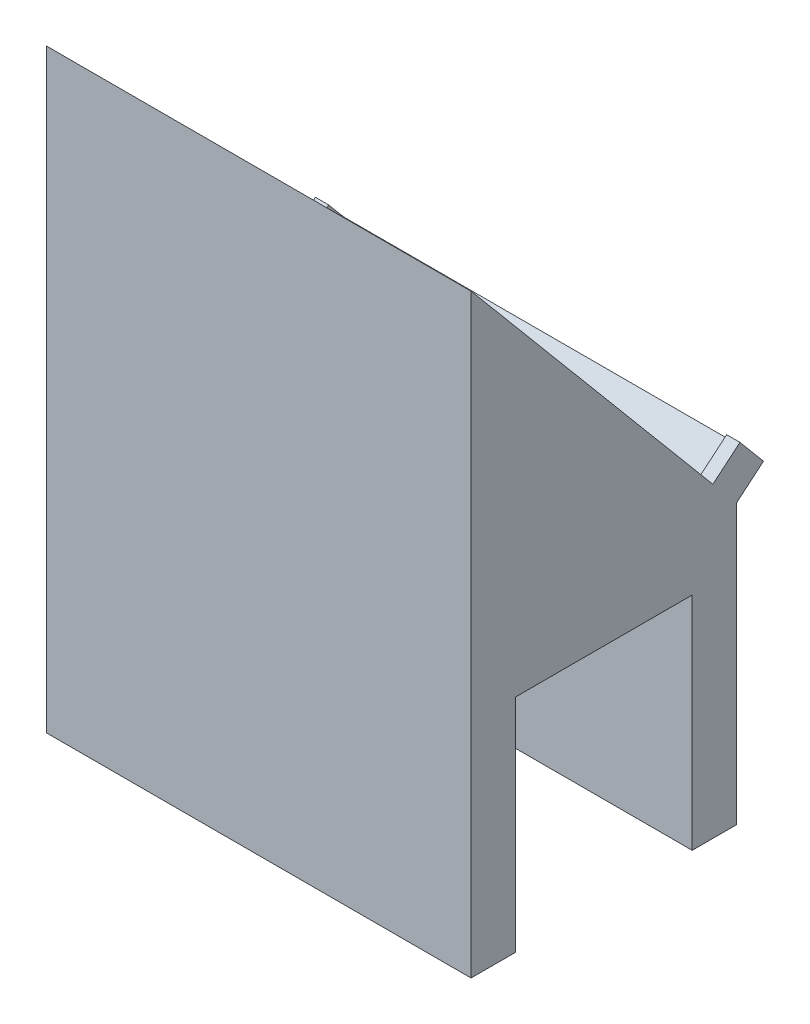
SolidWorks part; units mm, degrees
ref_plane "Спереди" through (0, 0, 0) normal (0, 0, 1) x (1, 0, 0)
ref_plane "Сверху" through (0, 0, 0) normal (0, 1, 0) x (1, 0, 0)
ref_plane "Справа" through (0, 0, 0) normal (1, 0, 0) x (0, 0, -1)
sketch "Эскиз1" plane through (0, 0, 0) normal (1, 0, 0) x (0, 0, -1)
  line L0 (0, 109.2621) -> (60, 37.7569)
  line L1 (60, 37.7569) -> (60, -25.2429)
  line L2 (60, -25.2429) -> (50, -25.2429)
  line L3 (0, -25.2429) -> (0, 109.2621)
  line L4 (10, -25.2429) -> (10, 24.7571)
  line L5 (10, 24.7571) -> (50, 24.7571)
  line L6 (50, 24.7571) -> (50, -25.2429)
  line L7 (10, -25.2429) -> (0, -25.2429)
  dimension "D1" = 140
  dimension "D2" = 60
  dimension "D3" = 10
  dimension "D4" = 10
  dimension "D5" = 50
extrude "Бобышка-Вытянуть1" add sketch "Эскиз1" along normal blind 96 contours L0 L1 L2 L6 L5 L4 L7 L3
sketch "Эскиз3" plane through (0, 45.1445, -53.8011) normal (0, 0.6428, -0.766) x (-1, 0, 0)
  line L0 (-96, 83.6996) -> (-96, -9.6438) construction
  line L1 (-96, -6.6438) -> (0, -6.6438)
  line L2 (-96, -6.6438) -> (-96, -9.6438)
  line L3 (-96, -9.6438) -> (0, -9.6438)
  line L4 (0, -6.6438) -> (0, -9.6438)
  line L5 (0, 83.6996) -> (0, -9.6438) construction
  line L6 (-96, -1.3554) -> (-93, -1.3554)
  line L7 (-96, -1.3554) -> (-96, -9.6438)
  line L8 (-96, -9.6438) -> (-93, -9.6438)
  line L9 (-93, -1.3554) -> (-93, -9.6438)
  line L10 (0, -1.3554) -> (-3, -1.3554)
  line L11 (0, -1.3554) -> (0, -9.6438)
  line L12 (0, -9.6438) -> (-3, -9.6438)
  line L13 (-3, -1.3554) -> (-3, -9.6438)
  line M10 (0, -9.6438) -> (0, 83.6996)
  line M12 (-96, 83.6996) -> (-96, -9.6438)
  line M13 (-96, -9.6438) -> (0, -9.6438)
  dimension "D1" = 3
  dimension "D2" = 3
  dimension "D3" = 3
extrude "Бобышка-Вытянуть2" add sketch "Эскиз3" along normal blind 8 contours L13 L1 L9 L3 | L1 L13 M13 M10 | L9 L1 M12 M13 | L9 L6 L1 M12
